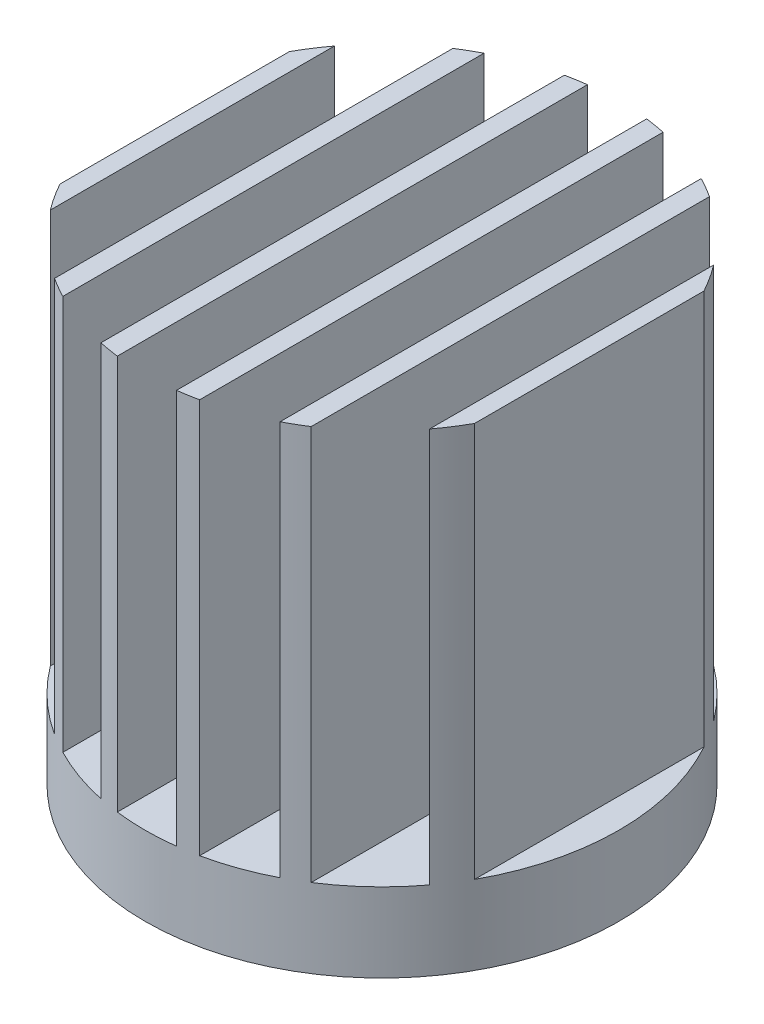
SolidWorks part; units mm, degrees
material "Plain Carbon Steel"
ref_plane "Front Plane" through (0, 0, 0) normal (0, 0, 1) x (1, 0, 0)
ref_plane "Top Plane" through (0, 0, 0) normal (0, 1, 0) x (1, 0, 0)
ref_plane "Right Plane" through (0, 0, 0) normal (1, 0, 0) x (0, 0, -1)
sketch "Sketch2" plane through (0, 0, 0) normal (0, 1, 0) x (1, 0, 0)
  circle A0 centre (0, 0) radius 60
  dimension "D1" = 120
extrude "Boss-Extrude1" add sketch "Sketch2" along normal blind 120
sketch "Sketch4" plane through (0, 0, 0) normal (0, 0, 1) x (1, 0, 0)
  line L0 (0, 20) -> (0, 0) construction
  line L1 (60, 120) -> (-60, 120) construction
  line L2 (-60, 0) -> (60, 0) construction
  line L6 (-60, 120) -> (-52.5, 120)
  line L10 (-52.5, 20) -> (-52.5, 120)
  line L16 (-32.5, 120) -> (-32.5, 20)
  line L18 (-27.5, 120) -> (-27.5, 20)
  line L20 (-12.5, 120) -> (-12.5, 20)
  line L22 (-7.5, 120) -> (-7.5, 20)
  line L23 (-52.5, 20) -> (-60, 20)
  line L25 (-48.0172, 120) -> (-48.0172, 20)
  line L27 (-60, 120) -> (-60, 0) construction
  line L28 (-60, 20) -> (-60, 120)
  line L29 (-48.0172, 120) -> (-32.5, 120)
  line L30 (-32.5, 20) -> (-48.0172, 20)
  line L31 (-27.5, 20) -> (-12.5, 20)
  line L33 (-27.5, 120) -> (-12.5, 120)
  line L34 (-7.5, 120) -> (7.5, 120)
  line L36 (7.5, 20) -> (-7.5, 20)
  line L37 (27.5, 120) -> (12.5, 120)
  line L38 (27.5, 20) -> (12.5, 20)
  line L39 (32.5, 20) -> (48.0172, 20)
  line L40 (48.0172, 120) -> (32.5, 120)
  line L41 (60, 20) -> (60, 120)
  line L42 (48.0172, 120) -> (48.0172, 20)
  line L43 (52.5, 20) -> (60, 20)
  line L44 (7.5, 120) -> (7.5, 20)
  line L45 (12.5, 120) -> (12.5, 20)
  line L46 (27.5, 120) -> (27.5, 20)
  line L47 (32.5, 120) -> (32.5, 20)
  line L48 (52.5, 20) -> (52.5, 120)
  line L49 (60, 120) -> (52.5, 120)
  dimension "D1" = 7.5
  dimension "D2" = 15
  dimension "D3" = 5
  dimension "D4" = 5
extrude "Cut-Extrude1" cut sketch "Sketch4" against normal mid plane 120
